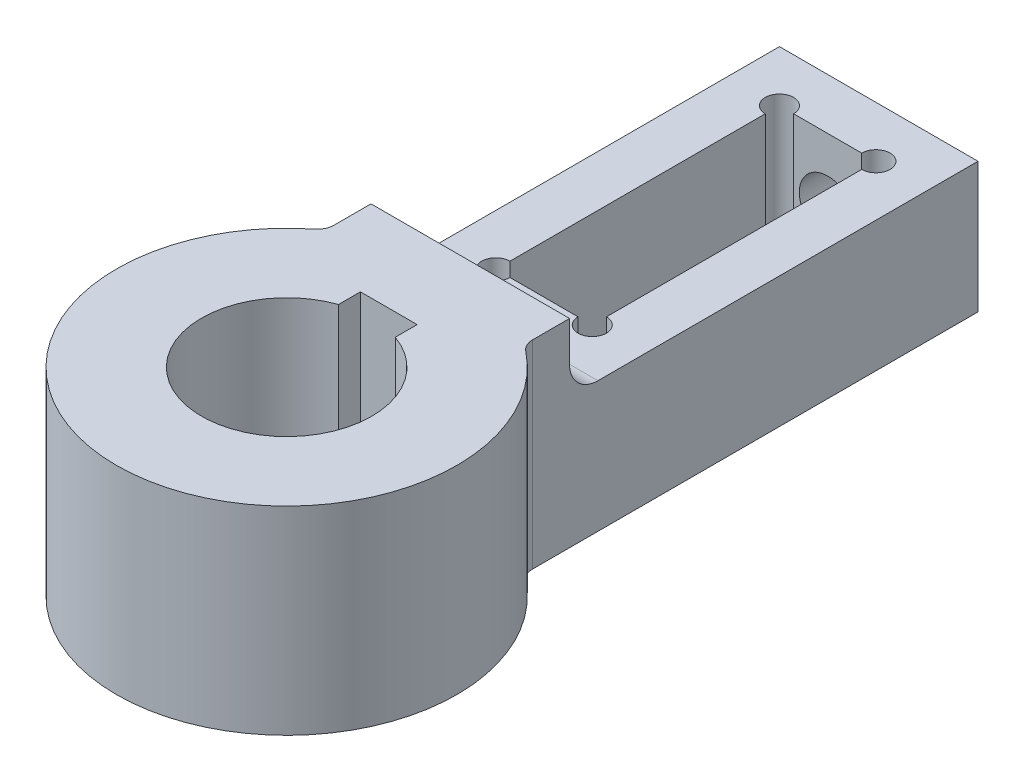
SolidWorks part; units mm, degrees
ref_plane "Front Plane" through (0, 0, 0) normal (0, 0, 1) x (1, 0, 0)
ref_plane "Top Plane" through (0, 0, 0) normal (0, 1, 0) x (1, 0, 0)
ref_plane "Right Plane" through (0, 0, 0) normal (1, 0, 0) x (0, 0, -1)
sketch "Sketch1" plane through (0, 0, 0) normal (0, 1, 0) x (1, 0, 0)
  line L0 (0, 0) -> (0, 104.367) construction
  line L1 (-17.5, 104.367) -> (17.5, 104.367)
  line L2 (17.5, 104.367) -> (17.5, 24.367)
  line L3 (-17.5, 104.367) -> (-17.5, 24.367)
  line L4 (-6, 95.367) -> (6, 95.367)
  line L5 (8.5, 92.867) -> (8.5, 47.867)
  line L6 (5, 18) -> (5, 14.1421)
  line L7 (-5, 18) -> (-5, 14.1421)
  line L8 (6, 45.367) -> (-6, 45.367)
  line L9 (-5, 18) -> (5, 18)
  line L10 (-8.5, 47.867) -> (-8.5, 92.867)
  line L11 (-8.5, 95.367) -> (-8.5, 70.367) construction
  line L12 (-8.5, 70.367) -> (3.7577, 70.367) construction
  arc A0 (-17.5, 24.367) -> (17.5, 24.367) centre (0, 0) ccw
  arc A1 (-6, 95.367) -> (-8.5, 92.867) centre (-8.5, 95.367) ccw
  arc A2 (-5, 14.1421) -> (5, 14.1421) centre (0, 0) ccw
  arc A3 (8.5, 92.867) -> (6, 95.367) centre (8.5, 95.367) ccw
  arc A4 (6, 45.367) -> (8.5, 47.867) centre (8.5, 45.367) ccw
  arc A5 (-8.5, 47.867) -> (-6, 45.367) centre (-8.5, 45.367) ccw
  dimension "D1" = 80
  dimension "D2" = 30
  dimension "D3" = 50
  dimension "D4" = 35
  dimension "D5" = 17
  dimension "D6" = 9
  dimension "D7" = 9
  dimension "D8" = 9
extrude "Boss-Extrude1" add sketch "Sketch1" along normal blind 35
sketch "Sketch2" plane through (0, 0, -104.367) normal (0, 0, -1) x (-1, 0, 0)
  line L0 (-17.5, 35) -> (-17.5, 0) construction
  line L1 (17.5, 35) -> (-17.5, 35)
  line L2 (17.5, 35) -> (17.5, 23)
  line L3 (17.5, 23) -> (-17.5, 23)
  line L4 (-17.5, 35) -> (-17.5, 23)
  dimension "D1" = 12
extrude "Cut-Extrude1" cut sketch "Sketch2" against normal blind 72
fillet "Fillet1" radius 5 1 edges at (0, 23, -32.367)
fillet "Fillet2" radius 3 2 edges at (-17.5, 17.5, -24.367) (17.5, 17.5, -24.367)
sketch "Sketch3" plane through (0, 0, -104.367) normal (0, 0, -1) x (-1, 0, 0)
  line L0 (0, 23) -> (0, 0) construction
  line L1 (17.5, 23) -> (-17.5, 23) construction
  circle A0 centre (0, 11.5) radius 5
extrude "Cut-Extrude2" cut sketch "Sketch3" against normal blind 65
